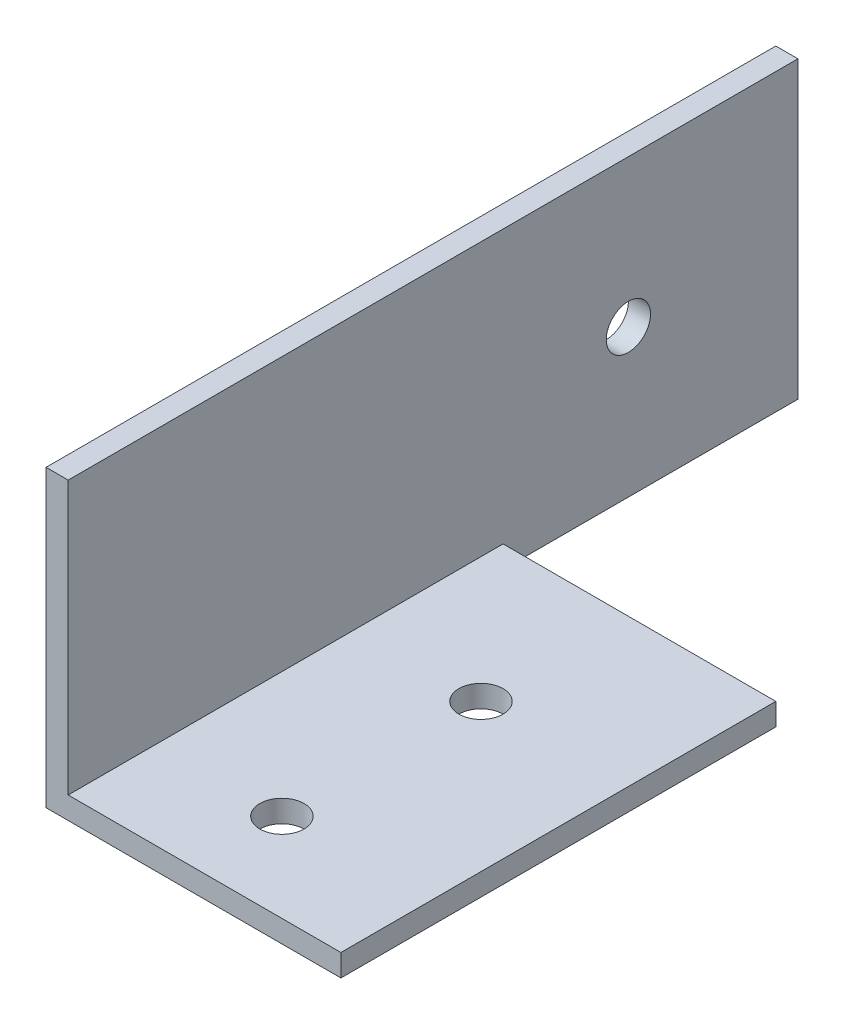
SolidWorks part; units mm, degrees
ref_plane "Plan de face" through (0, 0, 0) normal (0, 0, 1) x (1, 0, 0)
ref_plane "Plan de dessus" through (0, 0, 0) normal (0, 1, 0) x (1, 0, 0)
ref_plane "Plan de droite" through (0, 0, 0) normal (1, 0, 0) x (0, 0, -1)
sketch "Esquisse1" plane through (0, 0, 0) normal (0, 0, 1) x (1, 0, 0)
  line L0 (-24.9314, 6.5915) -> (-24.9314, -13.4085)
  line L1 (-24.9314, -13.4085) -> (-4.9314, -13.4085)
  line L2 (-4.9314, -13.4085) -> (-4.9314, -11.9085)
  line L3 (-4.9314, -11.9085) -> (-23.4314, -11.9085)
  line L4 (-23.4314, -11.9085) -> (-23.4314, 6.5915)
  line L5 (-23.4314, 6.5915) -> (-24.9314, 6.5915)
  dimension "D1" = 1.5
  dimension "D2" = 1.5
  dimension "D3" = 20
  dimension "D4" = 20
extrude "Extrusion1" add sketch "Esquisse1" along normal blind 49.5
sketch "Esquisse2" plane through (0, -11.9085, 0) normal (0, 1, 0) x (-1, 0, 0)
  line L0 (14.9314, 43.5) -> (14.9314, 30) construction
  line L1 (4.9314, 0) -> (23.4314, 0) construction
  line L3 (23.4314, 49.5) -> (23.4314, 0) construction
  line L4 (4.9314, 49.5) -> (23.4314, 49.5) construction
  line L8 (4.9314, 49.5) -> (4.9314, 0) construction
  line L9 (4.9314, 0) -> (23.4314, 0)
  line L10 (4.9314, 0) -> (4.9314, 20)
  line L11 (4.9314, 20) -> (23.4314, 20)
  line L12 (23.4314, 0) -> (23.4314, 20)
  circle A0 centre (14.9314, 43.5) radius 1.5
  circle A1 centre (14.9314, 30) radius 1.5
  dimension "D1" = 6
  dimension "D2" = 30
  dimension "D4" = 20
  dimension "D5" = 10
extrude "Extrusion2" cut sketch "Esquisse2" against normal blind 100
sketch "Esquisse3" plane through (-23.4314, 0, 0) normal (1, 0, 0) x (0, 0, -1)
  line L0 (-49.5, 6.5915) -> (0, 6.5915) construction
  line L2 (0, -13.4085) -> (0, 6.5915) construction
  circle A1 centre (-11.5, -3.4085) radius 1.5
  dimension "D1" = 10
  dimension "D2" = 11.5
extrude "Extrusion3" cut sketch "Esquisse3" against normal blind 100
